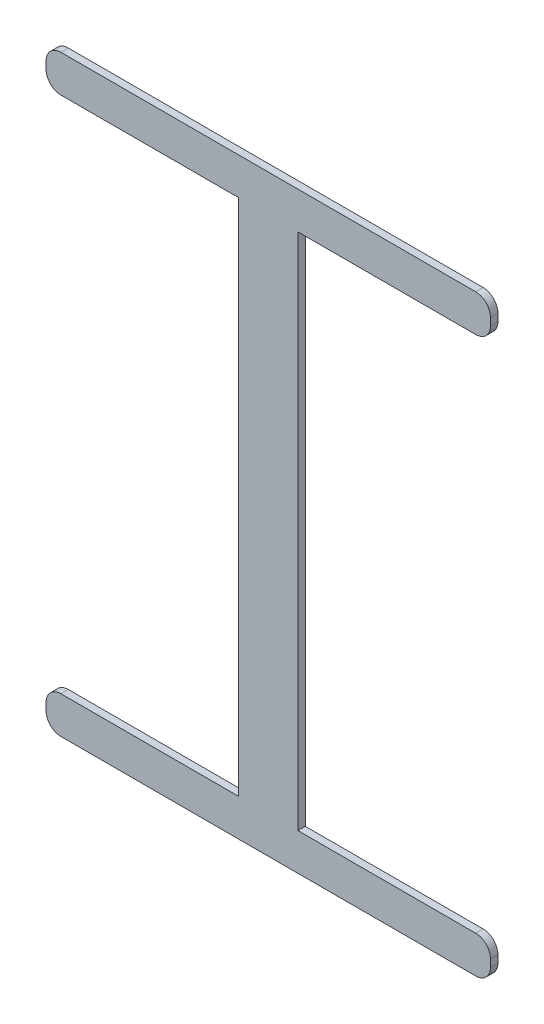
SolidWorks part; units mm, degrees
ref_plane "前视基准面" through (0, 0, 0) normal (0, 0, 1) x (1, 0, 0)
ref_plane "上视基准面" through (0, 0, 0) normal (0, 1, 0) x (1, 0, 0)
ref_plane "右视基准面" through (0, 0, 0) normal (1, 0, 0) x (0, 0, -1)
sketch "草图1" plane through (0, 0, 0) normal (0, 0, 1) x (1, 0, 0)
  line L0 (-56, 80) -> (56, 80)
  line L1 (60, 76) -> (60, 74)
  line L2 (56, 70) -> (8, 70)
  line L3 (8, 70) -> (8, -70)
  line L4 (0, -55) -> (0, 55) construction
  line L5 (-8, 70) -> (-8, -70)
  line L6 (-56, 70) -> (-8, 70)
  line L7 (-60, 76) -> (-60, 74)
  line L8 (55, 0) -> (-55, 0) construction
  line L9 (-60, -76) -> (-60, -74)
  line L10 (-56, -70) -> (-8, -70)
  line L11 (56, -70) -> (8, -70)
  line L12 (60, -76) -> (60, -74)
  line L13 (-56, -80) -> (56, -80)
  arc A0 (60, 76) -> (56, 80) centre (56, 76) ccw
  arc A1 (56, 70) -> (60, 74) centre (56, 74) ccw
  arc A2 (-56, 70) -> (-60, 74) centre (-56, 74) cw
  arc A3 (-60, 76) -> (-56, 80) centre (-56, 76) cw
  arc A4 (-60, -76) -> (-56, -80) centre (-56, -76) ccw
  arc A5 (-56, -70) -> (-60, -74) centre (-56, -74) ccw
  arc A6 (56, -70) -> (60, -74) centre (56, -74) cw
  arc A7 (60, -76) -> (56, -80) centre (56, -76) cw
  point P5 (0, -80)
  point P22 (0, 80)
  point P37 (-8, 0)
  point P38 (8, 0)
  dimension "D5" = 4
  dimension "D1" = 80
  dimension "D2" = 10
  dimension "D3" = 60
  dimension "D4" = 8
extrude "凸台-拉伸1" add sketch "草图1" along normal blind 2
